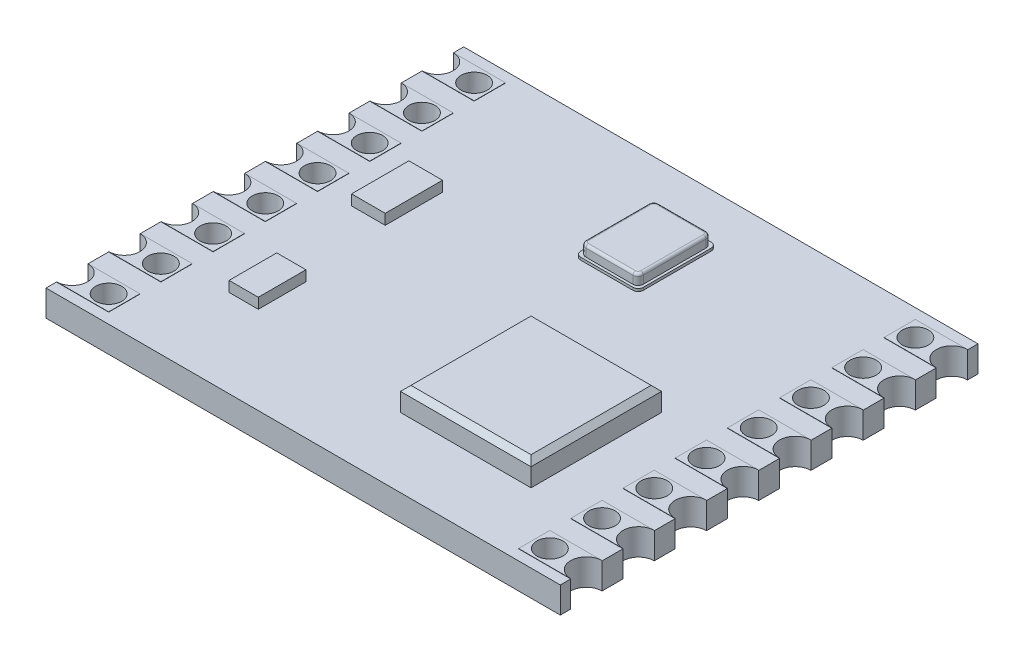
SolidWorks part; units mm, degrees
ref_plane "Front" through (0, 0, 0) normal (0, 0, 1) x (1, 0, 0)
ref_plane "Top" through (0, 0, 0) normal (0, 1, 0) x (1, 0, 0)
ref_plane "Right" through (0, 0, 0) normal (1, 0, 0) x (0, 0, -1)
sketch "Sketch1" plane through (0, 0, 0) normal (0, 1, 0) x (1, 0, 0)
  line L1 (0, 0) -> (19.7, 0)
  line L2 (0, 0) -> (0, 16)
  line L3 (0, 16) -> (19.7, 16)
  line L4 (19.7, 0) -> (19.7, 16)
  dimension "D1" = 19.7
  dimension "D2" = 16
extrude "Boss-Extrude1" add sketch "Sketch1" along normal blind 1
sketch "Sketch2" plane through (0, 1, 0) normal (0, 1, 0) x (1, 0, 0)
  line L0 (0, 16) -> (0, 0) construction
  line L1 (0, 15.6) -> (2, 15.6)
  line L2 (0, 15.6) -> (0, 14.4)
  line L3 (0, 14.4) -> (2, 14.4)
  line L4 (2, 15.6) -> (2, 14.4)
  line L5 (19.7, 16) -> (0, 16) construction
  line L6 (0, 13.6) -> (2, 13.6)
  line L7 (0, 13.6) -> (0, 12.4)
  line L8 (0, 12.4) -> (2, 12.4)
  line L9 (2, 13.6) -> (2, 12.4)
  line L10 (0, 11.6) -> (2, 11.6)
  line L11 (0, 11.6) -> (0, 10.4)
  line L12 (0, 10.4) -> (2, 10.4)
  line L13 (2, 11.6) -> (2, 10.4)
  line L14 (0, 9.6) -> (2, 9.6)
  line L15 (0, 9.6) -> (0, 8.4)
  line L16 (0, 8.4) -> (2, 8.4)
  line L17 (2, 9.6) -> (2, 8.4)
  line L18 (0, 7.6) -> (2, 7.6)
  line L19 (0, 7.6) -> (0, 6.4)
  line L20 (0, 6.4) -> (2, 6.4)
  line L21 (2, 7.6) -> (2, 6.4)
  line L22 (0, 5.6) -> (2, 5.6)
  line L23 (0, 5.6) -> (0, 4.4)
  line L24 (0, 4.4) -> (2, 4.4)
  line L25 (2, 5.6) -> (2, 4.4)
  line L26 (0, 3.6) -> (2, 3.6)
  line L27 (0, 3.6) -> (0, 2.4)
  line L28 (0, 2.4) -> (2, 2.4)
  line L29 (2, 3.6) -> (2, 2.4)
  line L30 (0, 1.6) -> (2, 1.6)
  line L31 (0, 1.6) -> (0, 0.4)
  line L32 (0, 0.4) -> (2, 0.4)
  line L33 (2, 1.6) -> (2, 0.4)
  line L34 (19.7, 0) -> (19.7, 16) construction
  line L35 (19.7, 15.6) -> (17.7, 15.6)
  line L36 (19.7, 15.6) -> (19.7, 14.4)
  line L37 (19.7, 14.4) -> (17.7, 14.4)
  line L38 (17.7, 15.6) -> (17.7, 14.4)
  line L39 (19.7, 13.6) -> (17.7, 13.6)
  line L40 (17.7, 13.6) -> (17.7, 12.4)
  line L41 (19.7, 12.4) -> (17.7, 12.4)
  line L42 (19.7, 13.6) -> (19.7, 12.4)
  line L43 (19.7, 11.6) -> (17.7, 11.6)
  line L44 (17.7, 11.6) -> (17.7, 10.4)
  line L45 (19.7, 10.4) -> (17.7, 10.4)
  line L46 (19.7, 11.6) -> (19.7, 10.4)
  line L47 (19.7, 9.6) -> (17.7, 9.6)
  line L48 (17.7, 9.6) -> (17.7, 8.4)
  line L49 (19.7, 8.4) -> (17.7, 8.4)
  line L50 (19.7, 9.6) -> (19.7, 8.4)
  line L51 (19.7, 7.6) -> (17.7, 7.6)
  line L52 (17.7, 7.6) -> (17.7, 6.4)
  line L53 (19.7, 6.4) -> (17.7, 6.4)
  line L54 (19.7, 7.6) -> (19.7, 6.4)
  line L55 (19.7, 5.6) -> (17.7, 5.6)
  line L56 (17.7, 5.6) -> (17.7, 4.4)
  line L57 (19.7, 4.4) -> (17.7, 4.4)
  line L58 (19.7, 5.6) -> (19.7, 4.4)
  line L59 (19.7, 3.6) -> (17.7, 3.6)
  line L60 (17.7, 3.6) -> (17.7, 2.4)
  line L61 (19.7, 2.4) -> (17.7, 2.4)
  line L62 (19.7, 3.6) -> (19.7, 2.4)
  line L63 (19.7, 1.6) -> (17.7, 1.6)
  line L64 (17.7, 1.6) -> (17.7, 0.4)
  line L65 (19.7, 0.4) -> (17.7, 0.4)
  line L66 (19.7, 1.6) -> (19.7, 0.4)
  dimension "D1" = 2
  dimension "D2" = 1.2
  dimension "D3" = 0.4
  dimension "D5" = 2
  dimension "D6" = 1.2
  dimension "D7" = 0.4
  dimension "D4" = 8
  dimension "D8" = 8
extrude "Boss-Extrude2" add sketch "Sketch2" along normal blind 0.01
sketch "Sketch3" plane through (0, 1.01, 0) normal (0, 1, 0) x (1, 0, 0)
  line L0 (0, 15.6) -> (0, 14.4) construction
  line L1 (0, 14.4) -> (2, 14.4) construction
  line L2 (0, 15.6) -> (0, 14.4)
  line L3 (2, 15.6) -> (0, 15.6) construction
  line L6 (2, 14.4) -> (2, 15.6) construction
  line L7 (0, 13.6) -> (0, 12.4)
  line L8 (0, 11.6) -> (0, 10.4)
  line L9 (0, 9.6) -> (0, 8.4)
  line L10 (0, 7.6) -> (0, 6.4)
  line L11 (0, 5.6) -> (0, 4.4)
  line L12 (0, 3.6) -> (0, 2.4)
  line L13 (0, 1.6) -> (0, 0.4)
  line L14 (19.7, 14.4) -> (19.7, 15.6) construction
  line L15 (19.7, 15.6) -> (17.7, 15.6) construction
  line L16 (17.7, 14.4) -> (19.7, 14.4) construction
  line L17 (19.7, 15.6) -> (19.7, 14.4)
  line L18 (17.7, 14.4) -> (19.7, 14.4) construction
  line L19 (17.7, 15.6) -> (17.7, 14.4) construction
  line L20 (19.7, 13.6) -> (19.7, 12.4)
  line L21 (19.7, 11.6) -> (19.7, 10.4)
  line L22 (19.7, 9.6) -> (19.7, 8.4)
  line L23 (19.7, 7.6) -> (19.7, 6.4)
  line L24 (19.7, 5.6) -> (19.7, 4.4)
  line L25 (19.7, 3.6) -> (19.7, 2.4)
  line L26 (19.7, 1.6) -> (19.7, 0.4)
  circle A0 centre (1.4, 15) radius 0.5
  arc A1 (0, 15.6) -> (0, 14.4) centre (0, 15) cw
  arc A2 (0, 13.6) -> (0, 12.4) centre (0, 13) cw
  circle A3 centre (1.4, 13) radius 0.5
  arc A4 (0, 11.6) -> (0, 10.4) centre (0, 11) cw
  circle A5 centre (1.4, 11) radius 0.5
  arc A6 (0, 9.6) -> (0, 8.4) centre (0, 9) cw
  circle A7 centre (1.4, 9) radius 0.5
  arc A8 (0, 7.6) -> (0, 6.4) centre (0, 7) cw
  circle A9 centre (1.4, 7) radius 0.5
  arc A10 (0, 5.6) -> (0, 4.4) centre (0, 5) cw
  circle A11 centre (1.4, 5) radius 0.5
  arc A12 (0, 3.6) -> (0, 2.4) centre (0, 3) cw
  circle A13 centre (1.4, 3) radius 0.5
  arc A14 (0, 1.6) -> (0, 0.4) centre (0, 1) cw
  circle A15 centre (1.4, 1) radius 0.5
  circle A16 centre (18.3, 15) radius 0.5
  arc A17 (19.7, 15.6) -> (19.7, 14.4) centre (19.7, 15) ccw
  circle A18 centre (18.3, 13) radius 0.5
  arc A19 (19.7, 13.6) -> (19.7, 12.4) centre (19.7, 13) ccw
  circle A20 centre (18.3, 11) radius 0.5
  arc A21 (19.7, 11.6) -> (19.7, 10.4) centre (19.7, 11) ccw
  circle A22 centre (18.3, 9) radius 0.5
  arc A23 (19.7, 9.6) -> (19.7, 8.4) centre (19.7, 9) ccw
  circle A24 centre (18.3, 7) radius 0.5
  arc A25 (19.7, 7.6) -> (19.7, 6.4) centre (19.7, 7) ccw
  circle A26 centre (18.3, 5) radius 0.5
  arc A27 (19.7, 5.6) -> (19.7, 4.4) centre (19.7, 5) ccw
  circle A28 centre (18.3, 3) radius 0.5
  arc A29 (19.7, 3.6) -> (19.7, 2.4) centre (19.7, 3) ccw
  circle A30 centre (18.3, 1) radius 0.5
  arc A31 (19.7, 1.6) -> (19.7, 0.4) centre (19.7, 1) ccw
  dimension "D1" = 1
  dimension "D5" = 0.6
  dimension "D6" = 0.6
  dimension "D7" = 1
  dimension "D2" = 0.6
  dimension "D3" = 0.6
  dimension "D4" = 8
  dimension "D8" = 8
extrude "Cut-Extrude1" cut sketch "Sketch3" against normal up to next (1.01 mm away)
sketch "Sketch4" plane through (0, 1, 0) normal (0, 1, 0) x (1, 0, 0)
  line L1 (10.9175, 7.6611) -> (15.9175, 7.6611)
  line L2 (10.9175, 7.6611) -> (10.9175, 2.6611)
  line L3 (10.9175, 2.6611) -> (15.9175, 2.6611)
  line L4 (15.9175, 7.6611) -> (15.9175, 2.6611)
  dimension "D1" = 5
  dimension "D2" = 5
extrude "Boss-Extrude3" add sketch "Sketch4" along normal blind 0.9
sketch "Sketch5" plane through (0, 1, 0) normal (0, 1, 0) x (1, 0, 0)
  line L1 (3.6527, 5.186) -> (4.7711, 5.186)
  line L2 (3.6527, 5.186) -> (3.6527, 3.3607)
  line L3 (3.6527, 3.3607) -> (4.7711, 3.3607)
  line L4 (4.7711, 5.186) -> (4.7711, 3.3607)
  line L5 (3.1285, 10.7704) -> (4.4166, 10.7704)
  line L6 (3.1285, 10.7704) -> (3.1285, 8.5768)
  line L7 (3.1285, 8.5768) -> (4.4166, 8.5768)
  line L8 (4.4166, 10.7704) -> (4.4166, 8.5768)
extrude "Boss-Extrude4" add sketch "Sketch5" along normal blind 0.4
sketch "Sketch6" plane through (0, 1, 0) normal (0, 1, 0) x (1, 0, 0)
  line L1 (9.3149, 14.1645) -> (11.3149, 14.1645)
  line L2 (9.1149, 13.9645) -> (9.1149, 11.3645)
  line L3 (9.3149, 11.1645) -> (11.3149, 11.1645)
  line L4 (11.5149, 13.9645) -> (11.5149, 11.3645)
  arc A0 (9.1149, 11.3645) -> (9.3149, 11.1645) centre (9.3149, 11.3645) ccw
  arc A1 (11.3149, 11.1645) -> (11.5149, 11.3645) centre (11.3149, 11.3645) ccw
  arc A2 (11.3149, 14.1645) -> (11.5149, 13.9645) centre (11.3149, 13.9645) cw
  arc A3 (9.3149, 14.1645) -> (9.1149, 13.9645) centre (9.3149, 13.9645) ccw
  point P6 (9.1149, 11.1645)
  point P11 (11.5149, 14.1645)
  point P14 (9.1149, 14.1645)
  dimension "D3" = 0.2
  dimension "D1" = 2.4
  dimension "D2" = 3
extrude "Boss-Extrude5" add sketch "Sketch6" along normal blind 0.1
sketch "Sketch7" plane through (0, 1.1, 0) normal (0, 1, 0) x (1, 0, 0)
  line L0 (9.1149, 13.9645) -> (9.1149, 11.3645) construction
  line L1 (9.4149, 14.0645) -> (11.2149, 14.0645)
  line L2 (9.2149, 13.8645) -> (9.2149, 11.4645)
  line L3 (9.4149, 11.2645) -> (11.2149, 11.2645)
  line L4 (11.4149, 13.8645) -> (11.4149, 11.4645)
  line L5 (11.3149, 14.1645) -> (9.3149, 14.1645) construction
  line L6 (11.5149, 11.3645) -> (11.5149, 13.9645) construction
  line L7 (9.3149, 11.1645) -> (11.3149, 11.1645) construction
  arc A0 (11.2149, 14.0645) -> (11.4149, 13.8645) centre (11.2149, 13.8645) cw
  arc A1 (11.2149, 11.2645) -> (11.4149, 11.4645) centre (11.2149, 11.4645) ccw
  arc A2 (9.2149, 11.4645) -> (9.4149, 11.2645) centre (9.4149, 11.4645) ccw
  arc A3 (9.4149, 14.0645) -> (9.2149, 13.8645) centre (9.4149, 13.8645) ccw
  dimension "D5" = 0.2
  dimension "D1" = 0.1
  dimension "D2" = 0.1
  dimension "D3" = 0.1
  dimension "D4" = 0.1
extrude "Boss-Extrude6" add sketch "Sketch7" along normal blind 0.4
fillet "Fillet1" radius 0.1 8 edges at (9.2149, 1.5, -12.6645) (9.2735, 1.5, -14.0059) (10.3149, 1.5, -14.0645) (11.3564, 1.5, -14.0059) (11.4149, 1.5, -12.6645) (11.3564, 1.5, -11.3231) (10.3149, 1.5, -11.2645) (9.2735, 1.5, -11.3231)
chamfer "Chamfer1" distance 0.2 angle 45 4 edges at (10.9175, 1.9, -5.1611) (13.4175, 1.9, -7.6611) (15.9175, 1.9, -5.1611) (13.4175, 1.9, -2.6611)
